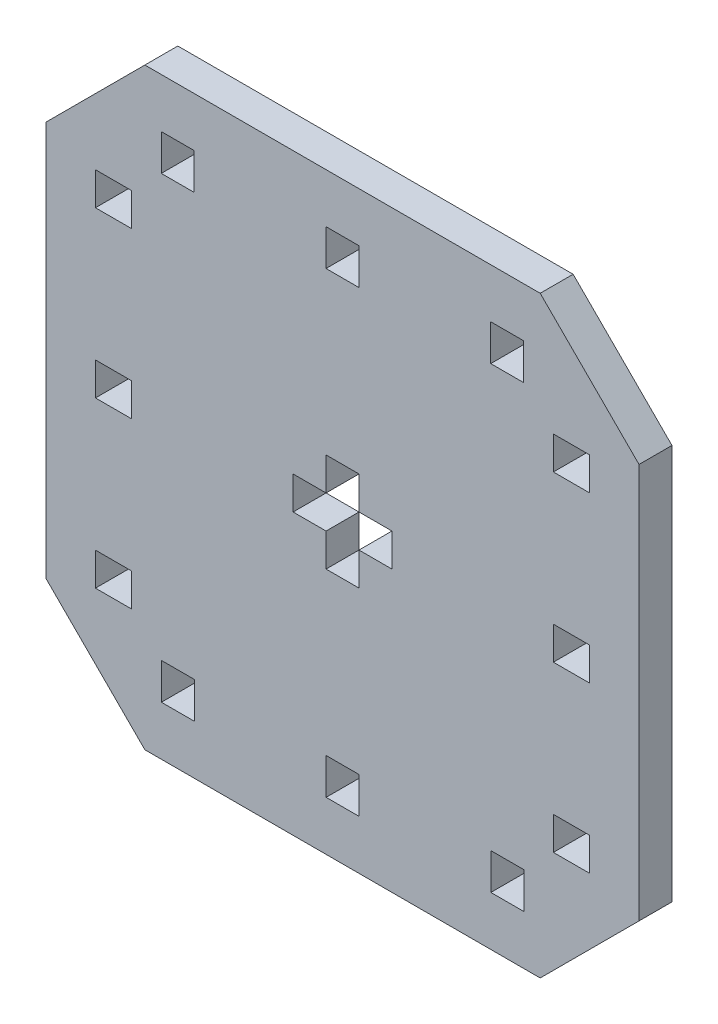
SolidWorks part; units mm, degrees
ref_plane "Front Plane" through (0, 0, 0) normal (0, 0, 1) x (1, 0, 0)
ref_plane "Top Plane" through (0, 0, 0) normal (0, 1, 0) x (1, 0, 0)
ref_plane "Right Plane" through (0, 0, 0) normal (1, 0, 0) x (0, 0, -1)
sketch "Sketch1" plane through (0, 0, 0) normal (0, 0, 1) x (1, 0, 0)
  line L977 (115.5, 256.4944) -> (118.8, 256.4944)
  line L978 (118.8, 256.4944) -> (118.8, 253.4944)
  line L979 (118.8, 253.4944) -> (115.5, 253.4944)
  line L980 (115.5, 253.4944) -> (115.5, 256.4944)
  line L981 (136.5, 274.5) -> (136.5, 271.5)
  line L982 (136.5, 271.5) -> (133.5, 271.5)
  line L983 (133.5, 271.5) -> (133.5, 268.5)
  line L984 (133.5, 268.5) -> (136.5, 268.5)
  line L985 (136.5, 268.5) -> (136.5, 265.5)
  line L986 (136.5, 265.5) -> (139.5, 265.5)
  line L987 (139.5, 265.5) -> (139.5, 268.5)
  line L988 (139.5, 268.5) -> (142.5, 268.5)
  line L989 (142.5, 268.5) -> (142.5, 271.5)
  line L990 (142.5, 271.5) -> (139.5, 271.5)
  line L991 (139.5, 271.5) -> (139.5, 274.5)
  line L992 (139.5, 274.5) -> (136.5, 274.5)
  line L993 (165, 252) -> (156, 243)
  line L994 (156, 243) -> (120, 243)
  line L995 (120, 243) -> (111, 252)
  line L996 (111, 252) -> (111, 288)
  line L997 (111, 288) -> (120, 297)
  line L998 (120, 297) -> (156, 297)
  line L999 (156, 297) -> (165, 288)
  line L1000 (165, 288) -> (165, 252)
  line L1001 (115.5, 286.4944) -> (118.8, 286.4944)
  line L1002 (118.8, 286.4944) -> (118.8, 283.4944)
  line L1003 (118.8, 283.4944) -> (115.5, 283.4944)
  line L1004 (115.5, 283.4944) -> (115.5, 286.4944)
  line L1005 (115.5, 271.4944) -> (118.8, 271.4944)
  line L1006 (118.8, 271.4944) -> (118.8, 268.4944)
  line L1007 (118.8, 268.4944) -> (115.5, 268.4944)
  line L1008 (115.5, 268.4944) -> (115.5, 271.4944)
  line L1009 (121.5056, 247.5) -> (121.5056, 250.8)
  line L1010 (121.5056, 250.8) -> (124.5056, 250.8)
  line L1011 (124.5056, 250.8) -> (124.5056, 247.5)
  line L1012 (124.5056, 247.5) -> (121.5056, 247.5)
  line L1013 (160.5, 253.5056) -> (157.2, 253.5056)
  line L1014 (157.2, 253.5056) -> (157.2, 256.5056)
  line L1015 (157.2, 256.5056) -> (160.5, 256.5056)
  line L1016 (160.5, 256.5056) -> (160.5, 253.5056)
  line L1017 (154.4944, 292.5) -> (154.4944, 289.2)
  line L1018 (154.4944, 289.2) -> (151.4944, 289.2)
  line L1019 (151.4944, 289.2) -> (151.4944, 292.5)
  line L1020 (151.4944, 292.5) -> (154.4944, 292.5)
  line L1021 (136.5056, 247.5) -> (136.5056, 250.8)
  line L1022 (136.5056, 250.8) -> (139.5056, 250.8)
  line L1023 (139.5056, 250.8) -> (139.5056, 247.5)
  line L1024 (139.5056, 247.5) -> (136.5056, 247.5)
  line L1025 (151.5056, 247.5) -> (151.5056, 250.8)
  line L1026 (151.5056, 250.8) -> (154.5056, 250.8)
  line L1027 (154.5056, 250.8) -> (154.5056, 247.5)
  line L1028 (154.5056, 247.5) -> (151.5056, 247.5)
  line L1029 (160.5, 268.5056) -> (157.2, 268.5056)
  line L1030 (157.2, 268.5056) -> (157.2, 271.5056)
  line L1031 (157.2, 271.5056) -> (160.5, 271.5056)
  line L1032 (160.5, 271.5056) -> (160.5, 268.5056)
  line L1033 (160.5, 283.5056) -> (157.2, 283.5056)
  line L1034 (157.2, 283.5056) -> (157.2, 286.5056)
  line L1035 (157.2, 286.5056) -> (160.5, 286.5056)
  line L1036 (160.5, 286.5056) -> (160.5, 283.5056)
  line L1037 (139.4944, 292.5) -> (139.4944, 289.2)
  line L1038 (139.4944, 289.2) -> (136.4944, 289.2)
  line L1039 (136.4944, 289.2) -> (136.4944, 292.5)
  line L1040 (136.4944, 292.5) -> (139.4944, 292.5)
  line L1041 (124.4944, 292.5) -> (124.4944, 289.2)
  line L1042 (124.4944, 289.2) -> (121.4944, 289.2)
  line L1043 (121.4944, 289.2) -> (121.4944, 292.5)
  line L1044 (121.4944, 292.5) -> (124.4944, 292.5)
extrude "Boss-Extrude1" add sketch "Sketch1" along normal blind 3
